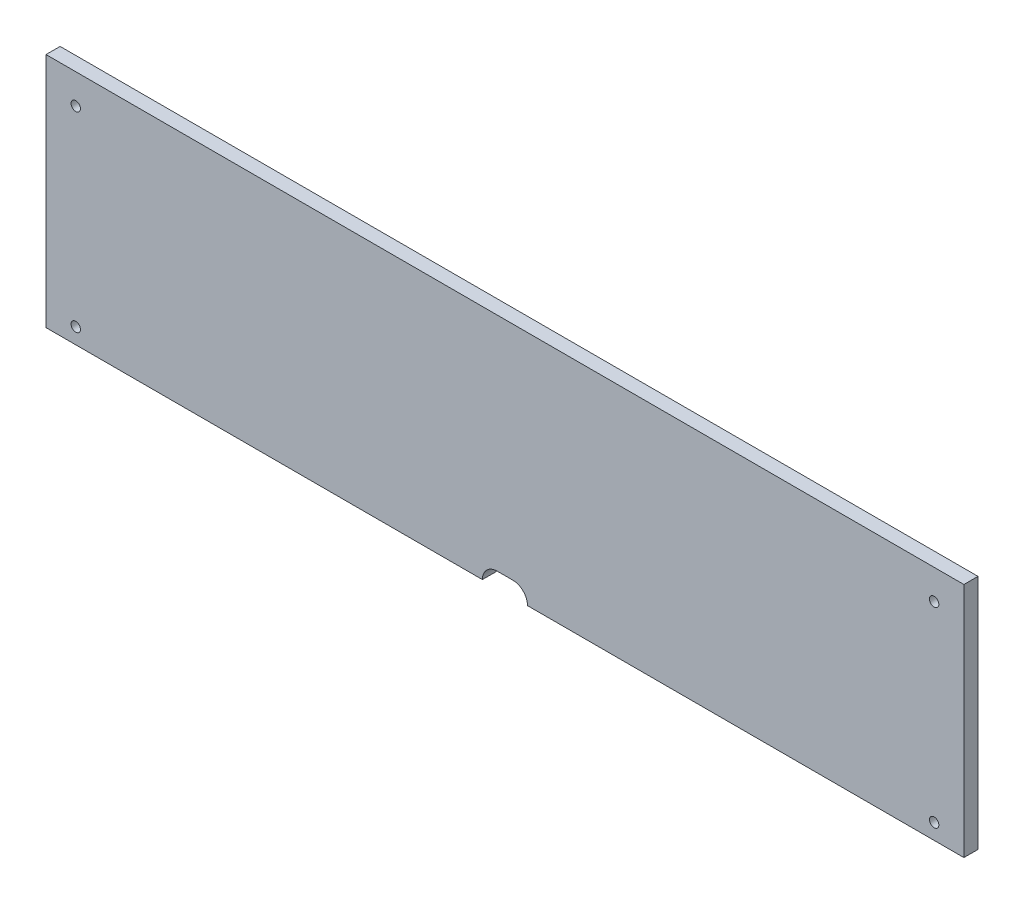
SolidWorks part; units mm, degrees
ref_plane "Front Plane" through (0, 0, 0) normal (0, 0, 1) x (1, 0, 0)
ref_plane "Top Plane" through (0, 0, 0) normal (0, 1, 0) x (1, 0, 0)
ref_plane "Right Plane" through (0, 0, 0) normal (1, 0, 0) x (0, 0, -1)
sketch "Sketch1" plane through (0, 0, 0) normal (0, 0, 1) x (1, 0, 0)
  line L1 (146.5, -37.75) -> (-146.5, -37.75)
  line L2 (146.5, -37.75) -> (146.5, 37.75)
  line L3 (146.5, 37.75) -> (-146.5, 37.75)
  line L4 (-146.5, -37.75) -> (-146.5, 37.75)
  line L5 (146.5, -37.75) -> (-146.5, 37.75) construction
  line L6 (146.5, 37.75) -> (-146.5, -37.75) construction
  point P0 (0, 0)
  dimension "D1" = 293
  dimension "D2" = 75.5
extrude "Boss-Extrude1" add sketch "Sketch1" along normal blind 4.5 contours L3 L4 L1 L2
sketch "Sketch2" plane through (0, 0, 4.5) normal (0, 0, 1) x (1, 0, 0)
  line L0 (146.5, 37.75) -> (137, 28.25) construction
  line L1 (146.5, 37.75) -> (137, 37.75) construction
  line L2 (146.5, 37.75) -> (146.5, 28.25) construction
  line L3 (146.5, 28.25) -> (137, 28.25) construction
  line L4 (137, 37.75) -> (137, 28.25) construction
  line L5 (0, 0) -> (0, -37.75) construction
  line L6 (-146.5, 37.75) -> (-137, 37.75) construction
  line L7 (-146.5, 37.75) -> (-146.5, 28.25) construction
  line L8 (-146.5, 28.25) -> (-137, 28.25) construction
  line L9 (-137, 37.75) -> (-137, 28.25) construction
  line L10 (146.5, -37.75) -> (-146.5, -37.75) construction
  line L11 (2.5, -37.75) -> (-2.5, -37.75) construction
  line L12 (2.5, -42.4499) -> (-2.5, -42.4499)
  line L13 (2.5, -33.0501) -> (-2.5, -33.0501)
  line L15 (-146.5, -37.75) -> (-137, -37.75) construction
  line L16 (-146.5, -37.75) -> (-146.5, -32.75) construction
  line L17 (-146.5, -32.75) -> (-137, -32.75) construction
  line L18 (-137, -37.75) -> (-137, -32.75) construction
  line L19 (146.5, -37.75) -> (137, -37.75) construction
  line L20 (146.5, -37.75) -> (146.5, -32.75) construction
  line L21 (146.5, -32.75) -> (137, -32.75) construction
  line L22 (137, -37.75) -> (137, -32.75) construction
  circle A0 centre (137, 28.25) radius 1.5
  circle A1 centre (-137, 28.25) radius 1.5
  arc A2 (2.5, -42.4499) -> (2.5, -33.0501) centre (2.5, -37.75) ccw
  arc A3 (-2.5, -33.0501) -> (-2.5, -42.4499) centre (-2.5, -37.75) ccw
  circle A4 centre (-137, -32.75) radius 1.5
  circle A5 centre (137, -32.75) radius 1.5
  point P19 (0, -37.75)
  dimension "D3" = 9.5
  dimension "D5" = 9.5
  dimension "D7" = 9.5
  dimension "D1" = 9.5
  dimension "D2" = 9.5
  dimension "D4" = 9.5
  dimension "D6" = 5
  dimension "D8" = 5
extrude "Cut-Extrude1" cut sketch "Sketch2" against normal up to next
